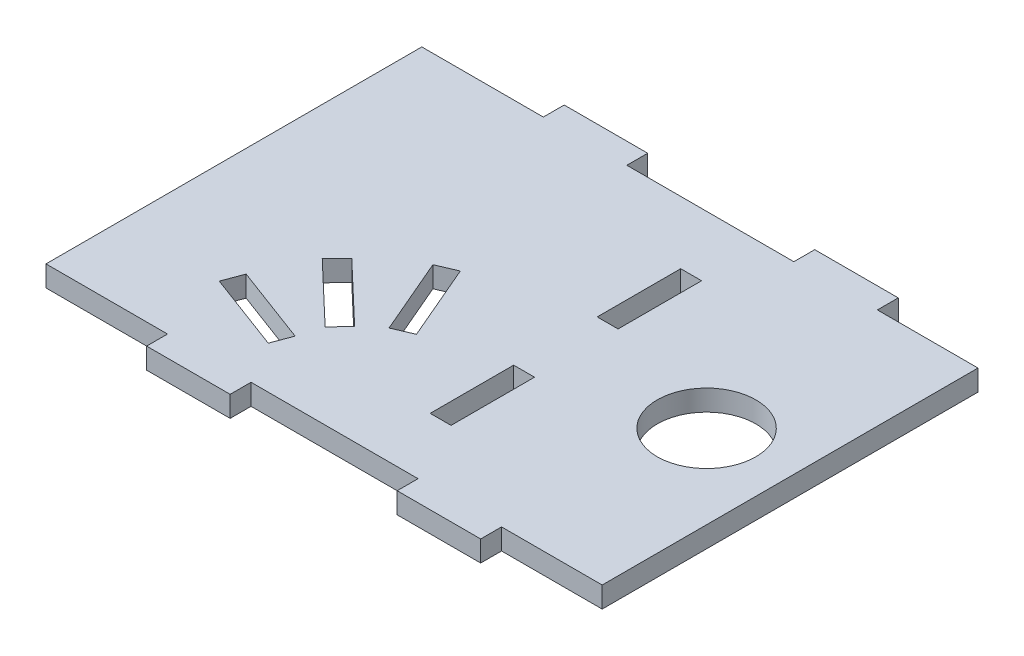
SolidWorks part; units mm, degrees
ref_plane "Front Plane" through (0, 0, 0) normal (0, 0, 1) x (1, 0, 0)
ref_plane "Top Plane" through (0, 0, 0) normal (0, 1, 0) x (1, 0, 0)
ref_plane "Right Plane" through (0, 0, 0) normal (1, 0, 0) x (0, 0, -1)
sketch "Sketch1" plane through (0, 0, 0) normal (0, 1, 0) x (1, 0, 0)
  line L0 (40.7024, 0) -> (40.7024, 70.4501) construction
  line L1 (0, 0) -> (15.3024, 0)
  line L3 (0, 57.15) -> (15.3024, 57.15)
  line L4 (81.4048, 0) -> (81.4048, 19.05)
  line L5 (0, 28.575) -> (84.5798, 28.575) construction
  line L6 (15.3024, 57.15) -> (15.3024, 60.325)
  line L7 (15.3024, 60.325) -> (28.0024, 60.325)
  line L8 (28.0024, 60.325) -> (28.0024, 57.15)
  line L9 (28.0024, 57.15) -> (53.4024, 57.15)
  line L10 (66.1024, 57.15) -> (66.1024, 60.325)
  line L11 (66.1024, 60.325) -> (53.4024, 60.325)
  line L12 (53.4024, 60.325) -> (53.4024, 57.15)
  line L13 (15.3024, -3.175) -> (28.0024, -3.175)
  line L14 (15.3024, 0) -> (15.3024, -3.175)
  line L15 (28.0024, -3.175) -> (28.0024, 0)
  line L16 (53.4024, -3.175) -> (53.4024, 0)
  line L17 (66.1024, 0) -> (66.1024, -3.175)
  line L18 (66.1024, -3.175) -> (53.4024, -3.175)
  line L19 (66.1024, 57.15) -> (81.4048, 57.15)
  line L20 (66.1024, 0) -> (81.4048, 0)
  line L21 (28.0024, 0) -> (53.4024, 0)
  line L29 (81.4048, 38.1) -> (81.4048, 57.15)
  line L30 (45.72, 22.225) -> (48.895, 22.225)
  line L31 (45.72, 47.625) -> (48.895, 47.625)
  line L32 (45.72, 47.625) -> (45.72, 34.925)
  line L33 (45.72, 34.925) -> (48.895, 34.925)
  line L34 (48.895, 47.625) -> (48.895, 34.925)
  line L35 (48.895, 9.525) -> (48.895, 22.225)
  line L36 (45.72, 9.525) -> (48.895, 9.525)
  line L37 (45.72, 9.525) -> (45.72, 22.225)
  line L38 (0, 29.3104) -> (26.3501, 29.3104) construction
  line L39 (26.3501, 29.3104) -> (31.3531, 17.6373)
  line L40 (31.3531, 17.6373) -> (34.2714, 18.8881)
  line L41 (34.2714, 18.8881) -> (29.2683, 30.5611)
  line L42 (29.2683, 30.5611) -> (26.3501, 29.3104)
  line L43 (0, 21.6789) -> (17.1531, 21.6789) construction
  line L44 (17.1531, 21.6789) -> (26.3501, 12.9207)
  line L45 (26.3501, 12.9207) -> (28.5396, 15.22)
  line L46 (28.5396, 15.22) -> (19.3426, 23.9782)
  line L47 (19.3426, 23.9782) -> (17.1531, 21.6789)
  line L48 (0, 10.9032) -> (12.2709, 10.9032) construction
  line L49 (0, 57.15) -> (-3.175, 57.15)
  line L50 (12.2709, 10.9032) -> (13.3828, 13.8771)
  line L51 (12.2709, 10.9032) -> (24.1666, 6.4555)
  line L52 (24.1666, 6.4555) -> (25.2785, 9.4295)
  line L53 (13.3828, 13.8771) -> (25.2785, 9.4295)
  line L54 (81.4048, 38.1) -> (81.4048, 19.05)
  line L55 (-3.175, 57.15) -> (-3.175, 0)
  line L56 (-3.175, 0) -> (0, 0)
  circle A0 centre (68.7048, 28.575) radius 7.5
  dimension "D13" = 15
  dimension "D1" = 81.4048
  dimension "D2" = 57.15
  dimension "D3" = 12.7
  dimension "D4" = 12.7
  dimension "D5" = 3.175
  dimension "D8" = 3.175
  dimension "D9" = 12.7
  dimension "D10" = 6.35
  dimension "D12" = 113.2
  dimension "D14" = 12.7
  dimension "D15" = 12.7
  dimension "D16" = 3.175
  dimension "D17" = 12.7
  dimension "D18" = 3.175
  dimension "D19" = 136.4
  dimension "D21" = 3.175
  dimension "D22" = 12.7
  dimension "D23" = 159.5
extrude "Boss-Extrude1" add sketch "Sketch1" along normal blind 3.175
